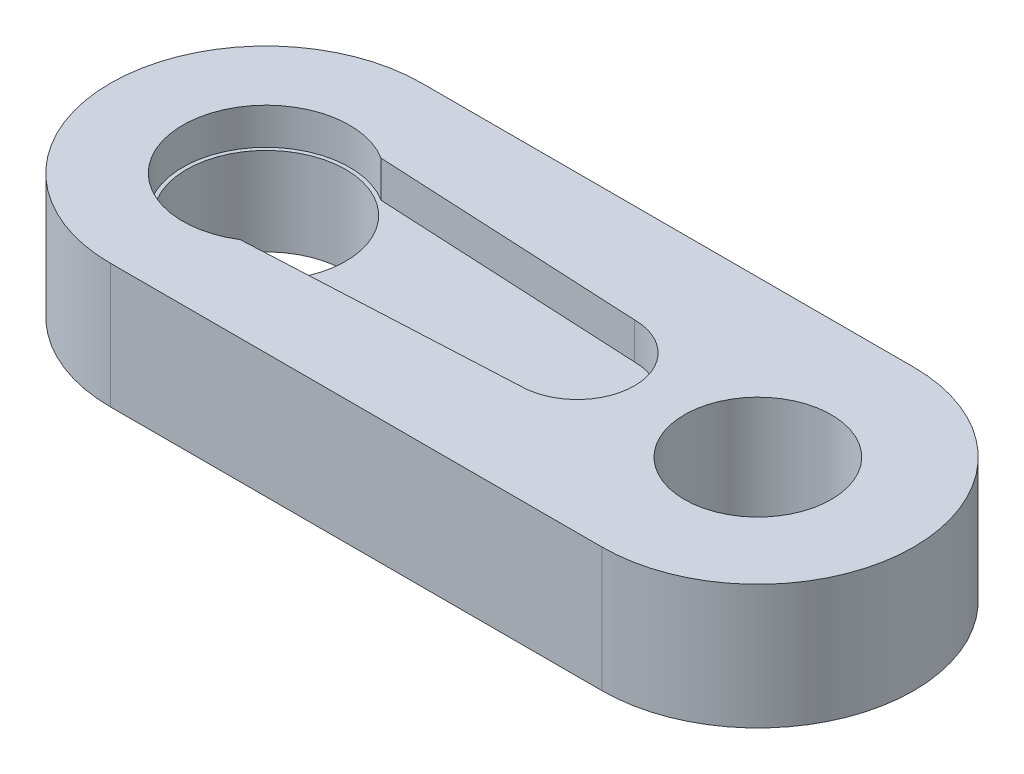
SolidWorks part; units mm, degrees
ref_plane "Front Plane" through (0, 0, 0) normal (0, 0, 1) x (1, 0, 0)
ref_plane "Top Plane" through (0, 0, 0) normal (0, 1, 0) x (1, 0, 0)
ref_plane "Right Plane" through (0, 0, 0) normal (1, 0, 0) x (0, 0, -1)
sketch "Sketch1" plane through (0, 0, 0) normal (0, 1, 0) x (1, 0, 0)
  line L0 (0, 0) -> (22.0896, 0) construction
  line L1 (0, 7) -> (22.0896, 7)
  line L2 (0, -7) -> (22.0896, -7)
  arc A0 (0, 7) -> (0, -7) centre (0, 0) ccw
  arc A1 (22.0896, -7) -> (22.0896, 7) centre (22.0896, 0) ccw
  point P3 (11.0448, 0)
  dimension "D1" = 7
extrude "Boss-Extrude1" add sketch "Sketch1" along normal blind 3.95
sketch "Sketch2" plane through (0, 0, 0) normal (0, -1, 0) x (1, 0, 0)
  circle A0 centre (0, 0) radius 3.575
  dimension "D1" = 7.15
extrude "Cut-Extrude1" cut sketch "Sketch2" against normal blind 3.95
sketch "Sketch3" plane through (0, 3.95, 0) normal (0, 1, 0) x (1, 0, 0)
  line L0 (1.9444, 3) -> (1.9444, -3) construction
  line L1 (3.575, 0) -> (16.375, 0) construction
  line L2 (1.9444, -3) -> (13.975, -2.4) construction
  line L3 (13.975, -2.4) -> (13.975, 2.4) construction
  line L4 (13.975, 2.4) -> (1.9444, 3) construction
  line L5 (13.9793, 2.57) -> (1.9979, 3.1675)
  line L6 (1.9979, -3.1675) -> (13.9793, -2.57)
  line L11 (0, -7) -> (22.0896, -7)
  line L12 (22.0896, 7) -> (0, 7)
  line L13 (0, -7) -> (22.0896, -7)
  line L14 (22.0896, 7) -> (0, 7)
  arc A1 (13.975, -2.4) -> (13.975, 2.4) centre (13.975, 0) ccw construction
  circle A2 centre (0, 0) radius 3.575 construction
  circle A3 centre (13.975, 0) radius 2.4 construction
  circle A4 centre (0, 0) radius 3.575 construction
  arc A5 (1.9444, -3) -> (1.9444, 3) centre (0, 0) cw construction
  arc A7 (1.9979, -3.1675) -> (1.9979, 3.1675) centre (0, 0) cw
  arc A8 (13.9793, -2.57) -> (13.9793, 2.57) centre (13.975, 0) ccw
  arc A12 (0, 7) -> (0, -7) centre (0, 0) ccw
  arc A13 (22.0896, -7) -> (22.0896, 7) centre (22.0896, 0) ccw
  arc A14 (0, 7) -> (0, -7) centre (0, 0) ccw
  arc A15 (22.0896, -7) -> (22.0896, 7) centre (22.0896, 0) ccw
  point P3 (0, 0)
  point P4 (1.9444, 0)
  point P18 (0, 0)
  dimension "D5" = 0
  dimension "D3" = 4.8
  dimension "D1" = 6
  dimension "D2" = 12.8
  dimension "D4" = 0.17
extrude "Boss-Extrude2" add sketch "Sketch3" along normal blind 1.64
sketch "Sketch4" plane through (0, 5.59, 0) normal (0, 1, 0) x (1, 0, 0)
  circle A0 centre (22.0896, 0) radius 3.3
  dimension "D1" = 6.6
extrude "Cut-Extrude2" cut sketch "Sketch4" against normal through all
